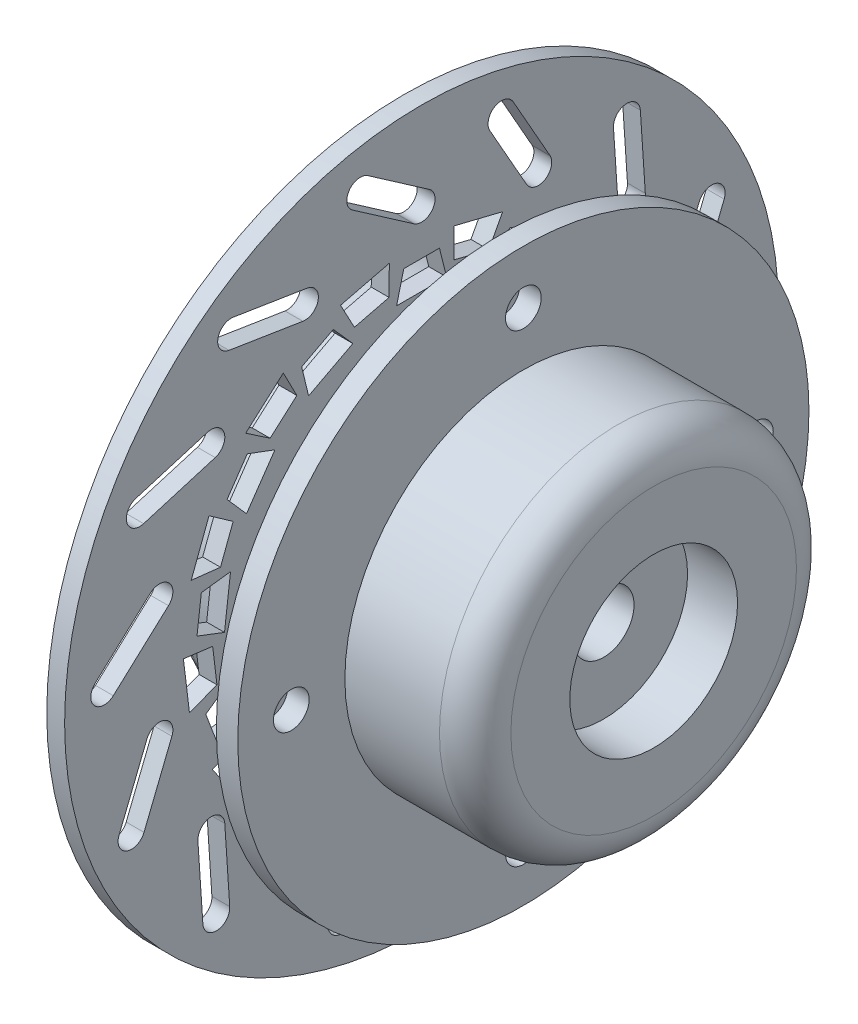
SolidWorks part; units mm, degrees
material "Stainless Steel (ferritic)"
ref_plane "Front Plane" through (0, 0, 0) normal (0, 0, 1) x (1, 0, 0)
ref_plane "Top Plane" through (0, 0, 0) normal (0, 1, 0) x (1, 0, 0)
ref_plane "Right Plane" through (0, 0, 0) normal (1, 0, 0) x (0, 0, -1)
sketch "Sketch1" plane through (0, 0, 0) normal (0, 1, 0) x (1, 0, 0)
  line L0 (0, 0) -> (0, 115.0534) construction
  line L1 (-76.2409, 0) -> (76.2409, 0) construction
  line L2 (-42.5, 0) -> (-42.5, 47.6639)
  line L3 (-39.5, 50.6639) -> (-27.5, 50.6639)
  line L4 (-27.5, 50.6639) -> (-27.5, 100)
  line L5 (-27.5, 100) -> (-22.5, 100)
  line L6 (-22.5, 100) -> (-22.5, 40)
  line L7 (-22.5, 40) -> (0, 40)
  line L8 (-42.5, 0) -> (42.5, 0)
  line L9 (0, 40) -> (0, 80)
  line L10 (0, 80) -> (6, 80)
  line L11 (6, 80) -> (6, 50)
  line L12 (6, 50) -> (32.5, 50)
  line L13 (42.5, 40) -> (42.5, 0)
  arc A0 (-39.5, 50.6639) -> (-42.5, 47.6639) centre (-39.5, 47.6639) ccw
  arc A1 (32.5, 50) -> (42.5, 40) centre (32.5, 40) cw
  point P6 (0, 0)
  point P22 (-42.5, 50.6639)
  dimension "D10" = 3
  dimension "D11" = 10
  dimension "D1" = 80
  dimension "D2" = 40
  dimension "D3" = 15
  dimension "D4" = 5
  dimension "D5" = 6
  dimension "D6" = 0
  dimension "D7" = 50
  dimension "D8" = 42.5
  dimension "D9" = 42.5
  dimension "D12" = 100
revolve "Revolve1" add sketch "Sketch1" angle 360 about L8
sketch "Sketch2" plane through (42.5, 0, 0) normal (1, 0, 0) x (0, 0, -1)
  circle A0 centre (0, 0) radius 8.5
  dimension "D1" = 17
extrude "Cut-Extrude1" cut sketch "Sketch2" against normal blind 75 contours A0
sketch "Sketch3" plane through (-42.5, 0, 0) normal (-1, 0, 0) x (0, 0, 1)
  circle A0 centre (0, 0) radius 23.5
  dimension "D1" = 47
extrude "Cut-Extrude2" cut sketch "Sketch3" against normal blind 14
sketch "Sketch4" plane through (42.5, 0, 0) normal (1, 0, 0) x (0, 0, -1)
  circle A0 centre (0, 0) radius 23.5
  dimension "D1" = 47
extrude "Cut-Extrude3" cut sketch "Sketch4" against normal blind 14
sketch "Sketch5" plane through (-27.5, 0, 0) normal (-1, 0, 0) x (0, 0, 1)
  line L0 (0, 50.6639) -> (0, 100) construction
  line L1 (-7, 54.7699) -> (7, 54.7699)
  line L2 (-5, 62.7699) -> (5, 62.7699)
  line L3 (-5, 62.7699) -> (-7, 54.7699)
  line L4 (5, 62.7699) -> (7, 54.7699)
  line L5 (0, -50.6639) -> (0, -100) construction
  line L6 (-5, -58.3563) -> (5, -58.3563)
  line L7 (-7.0317, -66.3563) -> (7.0317, -66.3563)
  line L8 (7.0317, -66.3563) -> (5, -58.3563)
  line L9 (-5, -58.3563) -> (-7.0317, -66.3563)
  line L10 (-31.5468, -49.3483) -> (-37.0636, -55.4878)
  line L11 (-37.0636, -55.4878) -> (-24.6111, -62.0234)
  line L12 (-24.6111, -62.0234) -> (-22.6922, -53.9956)
  line L13 (-31.5468, -49.3483) -> (-22.6922, -53.9956)
  line L14 (33.5979, 53.2563) -> (31.651, 45.2432)
  line L15 (19.2546, 51.7494) -> (31.651, 45.2432)
  line L16 (24.7433, 57.9036) -> (19.2546, 51.7494)
  line L17 (24.7433, 57.9036) -> (33.5979, 53.2563)
  line L18 (-50.8666, -29.0352) -> (-58.6046, -31.9077)
  line L19 (-58.6046, -31.9077) -> (-50.6157, -43.4816)
  line L20 (-50.6157, -43.4816) -> (-45.186, -37.2651)
  line L21 (-50.8666, -29.0352) -> (-45.186, -37.2651)
  line L22 (54.4989, 31.5424) -> (49.0512, 25.3519)
  line L23 (41.0983, 36.8737) -> (49.0512, 25.3519)
  line L24 (48.8183, 39.7723) -> (41.0983, 36.8737)
  line L25 (48.8183, 39.7723) -> (54.4989, 31.5424)
  line L26 (-58.5335, -2.0705) -> (-66.7201, -1.018)
  line L27 (-66.7201, -1.018) -> (-65.0249, -14.9788)
  line L28 (-65.0249, -14.9788) -> (-57.3281, -11.9976)
  line L29 (-58.5335, -2.0705) -> (-57.3281, -11.9976)
  line L30 (62.9149, 2.6025) -> (55.2143, -0.3472)
  line L31 (53.5268, 13.5507) -> (55.2143, -0.3472)
  line L32 (61.7095, 12.5296) -> (53.5268, 13.5507)
  line L33 (61.7095, 12.5296) -> (62.9149, 2.6025)
  line L34 (-52.7911, 25.3685) -> (-59.5508, 30.105)
  line L35 (-59.5508, 30.105) -> (-64.5377, 16.9555)
  line L36 (-64.5377, 16.9555) -> (-56.3371, 16.0184)
  line L37 (-52.7911, 25.3685) -> (-56.3371, 16.0184)
  line L38 (56.9178, -26.9336) -> (48.7285, -25.9668)
  line L39 (53.6929, -12.8765) -> (48.7285, -25.9668)
  line L40 (60.4639, -17.5834) -> (53.6929, -12.8765)
  line L41 (60.4639, -17.5834) -> (56.9178, -26.9336)
  line L42 (-34.9548, 46.9959) -> (-38.7391, 54.3313)
  line L43 (-38.7391, 54.3313) -> (-49.2657, 45.0055)
  line L44 (-49.2657, 45.0055) -> (-42.4399, 40.3647)
  line L45 (-34.9548, 46.9959) -> (-42.4399, 40.3647)
  line L46 (37.8816, -50.2995) -> (31.0796, -45.6377)
  line L47 (41.5587, -36.354) -> (31.0796, -45.6377)
  line L48 (45.3667, -43.6683) -> (41.5587, -36.354)
  line L49 (45.3667, -43.6683) -> (37.8816, -50.2995)
  line L50 (-9.1109, 57.8572) -> (-9.0528, 66.1109)
  line L51 (-9.0528, 66.1109) -> (-22.7075, 62.7453)
  line L52 (-22.7075, 62.7453) -> (-18.8203, 55.464)
  line L53 (-9.1109, 57.8572) -> (-18.8203, 55.464)
  line L54 (10.1671, -62.1425) -> (6.3107, -54.8536)
  line L55 (19.9039, -51.5031) -> (6.3107, -54.8536)
  line L56 (19.8765, -59.7493) -> (19.9039, -51.5031)
  line L57 (19.8765, -59.7493) -> (10.1671, -62.1425)
  line L58 (18.8203, 55.464) -> (22.7075, 62.7453)
  line L59 (22.7075, 62.7453) -> (9.0528, 66.1109)
  line L60 (9.0528, 66.1109) -> (9.1109, 57.8572)
  line L61 (18.8203, 55.464) -> (9.1109, 57.8572)
  line L62 (-19.8765, -59.7493) -> (-19.9039, -51.5031)
  line L63 (-6.3107, -54.8536) -> (-19.9039, -51.5031)
  line L64 (-10.1671, -62.1425) -> (-6.3107, -54.8536)
  line L65 (-10.1671, -62.1425) -> (-19.8765, -59.7493)
  line L66 (42.4399, 40.3647) -> (49.2657, 45.0055)
  line L67 (49.2657, 45.0055) -> (38.7391, 54.3313)
  line L68 (38.7391, 54.3313) -> (34.9548, 46.9959)
  line L69 (42.4399, 40.3647) -> (34.9548, 46.9959)
  line L70 (-45.3667, -43.6683) -> (-41.5587, -36.354)
  line L71 (-31.0796, -45.6377) -> (-41.5587, -36.354)
  line L72 (-37.8816, -50.2995) -> (-31.0796, -45.6377)
  line L73 (-37.8816, -50.2995) -> (-45.3667, -43.6683)
  line L74 (56.3371, 16.0184) -> (64.5377, 16.9555)
  line L75 (64.5377, 16.9555) -> (59.5508, 30.105)
  line L76 (59.5508, 30.105) -> (52.7911, 25.3685)
  line L77 (56.3371, 16.0184) -> (52.7911, 25.3685)
  line L78 (-60.4639, -17.5834) -> (-53.6929, -12.8765)
  line L79 (-48.7285, -25.9668) -> (-53.6929, -12.8765)
  line L80 (-56.9178, -26.9336) -> (-48.7285, -25.9668)
  line L81 (-56.9178, -26.9336) -> (-60.4639, -17.5834)
  line L82 (57.3281, -11.9976) -> (65.0249, -14.9788)
  line L83 (65.0249, -14.9788) -> (66.7201, -1.018)
  line L84 (66.7201, -1.018) -> (58.5335, -2.0705)
  line L85 (57.3281, -11.9976) -> (58.5335, -2.0705)
  line L86 (-61.7095, 12.5296) -> (-53.5268, 13.5507)
  line L87 (-55.2143, -0.3472) -> (-53.5268, 13.5507)
  line L88 (-62.9149, 2.6025) -> (-55.2143, -0.3472)
  line L89 (-62.9149, 2.6025) -> (-61.7095, 12.5296)
  line L90 (45.186, -37.2651) -> (50.6157, -43.4816)
  line L91 (50.6157, -43.4816) -> (58.6046, -31.9077)
  line L92 (58.6046, -31.9077) -> (50.8666, -29.0352)
  line L93 (45.186, -37.2651) -> (50.8666, -29.0352)
  line L94 (-48.8183, 39.7723) -> (-41.0983, 36.8737)
  line L95 (-49.0512, 25.3519) -> (-41.0983, 36.8737)
  line L96 (-54.4989, 31.5424) -> (-49.0512, 25.3519)
  line L97 (-54.4989, 31.5424) -> (-48.8183, 39.7723)
  line L98 (22.6922, -53.9956) -> (24.6111, -62.0234)
  line L99 (24.6111, -62.0234) -> (37.0636, -55.4878)
  line L100 (37.0636, -55.4878) -> (31.5468, -49.3483)
  line L101 (22.6922, -53.9956) -> (31.5468, -49.3483)
  line L102 (-24.7433, 57.9036) -> (-19.2546, 51.7494)
  line L103 (-31.651, 45.2432) -> (-19.2546, 51.7494)
  line L104 (-33.5979, 53.2563) -> (-31.651, 45.2432)
  line L105 (-33.5979, 53.2563) -> (-24.7433, 57.9036)
  circle A0 centre (0, 0) radius 50.6639 construction
  circle A1 centre (0, 0) radius 100 construction
  point P10 (0, 54.7699)
  point P13 (0, 62.7699)
  point P18 (0, -58.3563)
  point P21 (0, -66.3563)
  point P119 (0, 0)
  dimension "D1" = 8
  dimension "D2" = 8
  dimension "D3" = 13
extrude "Cut-Extrude4" cut sketch "Sketch5" against normal blind 15
sketch "Sketch6" plane through (-27.5, 0, 0) normal (-1, 0, 0) x (0, 0, 1)
  line L0 (0, 50.6639) -> (0, 100) construction
  line L1 (0, 75.332) -> (17.1894, 87.2629) construction
  line L2 (-2.1485, 78.4273) -> (15.041, 90.3583)
  line L3 (2.1485, 72.2366) -> (19.3379, 84.1675)
  line L4 (32.6853, 67.8717) -> (53.3491, 71.1629) construction
  line L5 (32.0927, 71.5928) -> (52.7564, 74.884)
  line L6 (33.278, 64.1507) -> (53.9418, 67.4419)
  line L7 (58.8969, 46.9687) -> (78.9423, 40.9683) construction
  line L8 (59.9774, 50.5784) -> (80.0228, 44.5779)
  line L9 (57.8164, 43.359) -> (77.8618, 37.3586)
  line L10 (73.4432, 16.7629) -> (88.9, 2.6593) construction
  line L11 (75.9829, 19.5463) -> (91.4397, 5.4427)
  line L12 (70.9035, 13.9796) -> (86.3603, -0.124)
  line L13 (73.4432, -16.7629) -> (81.25, -36.1763) construction
  line L14 (76.9391, -15.3571) -> (84.7459, -34.7705)
  line L15 (69.9474, -18.1687) -> (77.7542, -37.5821)
  line L16 (58.8969, -46.9687) -> (57.5074, -67.8468) construction
  line L17 (62.6565, -47.2189) -> (61.267, -68.097)
  line L18 (55.1373, -46.7185) -> (53.7478, -67.5966)
  line L19 (32.6853, -67.8717) -> (22.3748, -86.0794) construction
  line L20 (35.964, -69.7284) -> (25.6535, -87.936)
  line L21 (29.4066, -66.0151) -> (19.0961, -84.2227)
  line L22 (0, -75.332) -> (-17.1894, -87.2629) construction
  line L23 (2.1485, -78.4273) -> (-15.041, -90.3583)
  line L24 (-2.1485, -72.2366) -> (-19.3379, -84.1675)
  line L25 (-32.6853, -67.8717) -> (-53.3491, -71.1629) construction
  line L26 (-32.0927, -71.5928) -> (-52.7564, -74.884)
  line L27 (-33.278, -64.1507) -> (-53.9418, -67.4419)
  line L28 (-58.8969, -46.9687) -> (-78.9423, -40.9683) construction
  line L29 (-59.9774, -50.5784) -> (-80.0228, -44.5779)
  line L30 (-57.8164, -43.359) -> (-77.8618, -37.3586)
  line L31 (-73.4432, -16.7629) -> (-88.9, -2.6593) construction
  line L32 (-75.9829, -19.5463) -> (-91.4397, -5.4427)
  line L33 (-70.9035, -13.9796) -> (-86.3603, 0.124)
  line L34 (-73.4432, 16.7629) -> (-81.25, 36.1763) construction
  line L35 (-76.9391, 15.3571) -> (-84.7459, 34.7705)
  line L36 (-69.9474, 18.1687) -> (-77.7542, 37.5821)
  line L37 (-58.8969, 46.9687) -> (-57.5074, 67.8468) construction
  line L38 (-62.6565, 47.2189) -> (-61.267, 68.097)
  line L39 (-55.1373, 46.7185) -> (-53.7478, 67.5966)
  line L40 (-32.6853, 67.8717) -> (-22.3748, 86.0794) construction
  line L41 (-35.964, 69.7284) -> (-25.6535, 87.936)
  line L42 (-29.4066, 66.0151) -> (-19.0961, 84.2227)
  circle A0 centre (0, 0) radius 50.6639 construction
  circle A1 centre (0, 0) radius 50.6639 construction
  circle A2 centre (0, 0) radius 100 construction
  arc A3 (-2.1485, 78.4273) -> (2.1485, 72.2366) centre (0, 75.332) ccw
  arc A4 (19.3379, 84.1675) -> (15.041, 90.3583) centre (17.1894, 87.2629) ccw
  arc A5 (32.0927, 71.5928) -> (33.278, 64.1507) centre (32.6853, 67.8717) ccw
  arc A6 (53.9418, 67.4419) -> (52.7564, 74.884) centre (53.3491, 71.1629) ccw
  arc A7 (59.9774, 50.5784) -> (57.8164, 43.359) centre (58.8969, 46.9687) ccw
  arc A8 (77.8618, 37.3586) -> (80.0228, 44.5779) centre (78.9423, 40.9683) ccw
  arc A9 (75.9829, 19.5463) -> (70.9035, 13.9796) centre (73.4432, 16.7629) ccw
  arc A10 (86.3603, -0.124) -> (91.4397, 5.4427) centre (88.9, 2.6593) ccw
  arc A11 (76.9391, -15.3571) -> (69.9474, -18.1687) centre (73.4432, -16.7629) ccw
  arc A12 (77.7542, -37.5821) -> (84.7459, -34.7705) centre (81.25, -36.1763) ccw
  arc A13 (62.6565, -47.2189) -> (55.1373, -46.7185) centre (58.8969, -46.9687) ccw
  arc A14 (53.7478, -67.5966) -> (61.267, -68.097) centre (57.5074, -67.8468) ccw
  arc A15 (35.964, -69.7284) -> (29.4066, -66.0151) centre (32.6853, -67.8717) ccw
  arc A16 (19.0961, -84.2227) -> (25.6535, -87.936) centre (22.3748, -86.0794) ccw
  arc A17 (2.1485, -78.4273) -> (-2.1485, -72.2366) centre (0, -75.332) ccw
  arc A18 (-19.3379, -84.1675) -> (-15.041, -90.3583) centre (-17.1894, -87.2629) ccw
  arc A19 (-32.0927, -71.5928) -> (-33.278, -64.1507) centre (-32.6853, -67.8717) ccw
  arc A20 (-53.9418, -67.4419) -> (-52.7564, -74.884) centre (-53.3491, -71.1629) ccw
  arc A21 (-59.9774, -50.5784) -> (-57.8164, -43.359) centre (-58.8969, -46.9687) ccw
  arc A22 (-77.8618, -37.3586) -> (-80.0228, -44.5779) centre (-78.9423, -40.9683) ccw
  arc A23 (-75.9829, -19.5463) -> (-70.9035, -13.9796) centre (-73.4432, -16.7629) ccw
  arc A24 (-86.3603, 0.124) -> (-91.4397, -5.4427) centre (-88.9, -2.6593) ccw
  arc A25 (-76.9391, 15.3571) -> (-69.9474, 18.1687) centre (-73.4432, 16.7629) ccw
  arc A26 (-77.7542, 37.5821) -> (-84.7459, 34.7705) centre (-81.25, 36.1763) ccw
  arc A27 (-62.6565, 47.2189) -> (-55.1373, 46.7185) centre (-58.8969, 46.9687) ccw
  arc A28 (-53.7478, 67.5966) -> (-61.267, 68.097) centre (-57.5074, 67.8468) ccw
  arc A29 (-35.964, 69.7284) -> (-29.4066, 66.0151) centre (-32.6853, 67.8717) ccw
  arc A30 (-19.0961, 84.2227) -> (-25.6535, 87.936) centre (-22.3748, 86.0794) ccw
  point P11 (8.5947, 81.2974)
  point P18 (43.0172, 69.5173)
  point P27 (68.9196, 43.9685)
  point P34 (81.1716, 9.7111)
  point P41 (77.3466, -26.4696)
  point P48 (58.2022, -57.4077)
  point P55 (27.5301, -76.9756)
  point P62 (-8.5947, -81.2974)
  point P69 (-43.0172, -69.5173)
  point P76 (-68.9196, -43.9685)
  point P83 (-81.1716, -9.7111)
  point P90 (-77.3466, 26.4696)
  point P97 (-58.2022, 57.4077)
  point P104 (-27.5301, 76.9756)
  point P109 (0, 0)
  dimension "D1" = 14
extrude "Cut-Extrude5" cut sketch "Sketch6" against normal blind 15
sketch "Sketch7" plane through (6, 0, 0) normal (1, 0, 0) x (0, 0, -1)
  circle A0 centre (0, 0) radius 65 construction
  circle A1 centre (65, 0) radius 5
  circle A2 centre (0, -65) radius 5
  circle A3 centre (-65, 0) radius 5
  circle A4 centre (0, 65) radius 5
extrude "Cut-Extrude6" cut sketch "Sketch7" against normal blind 15
